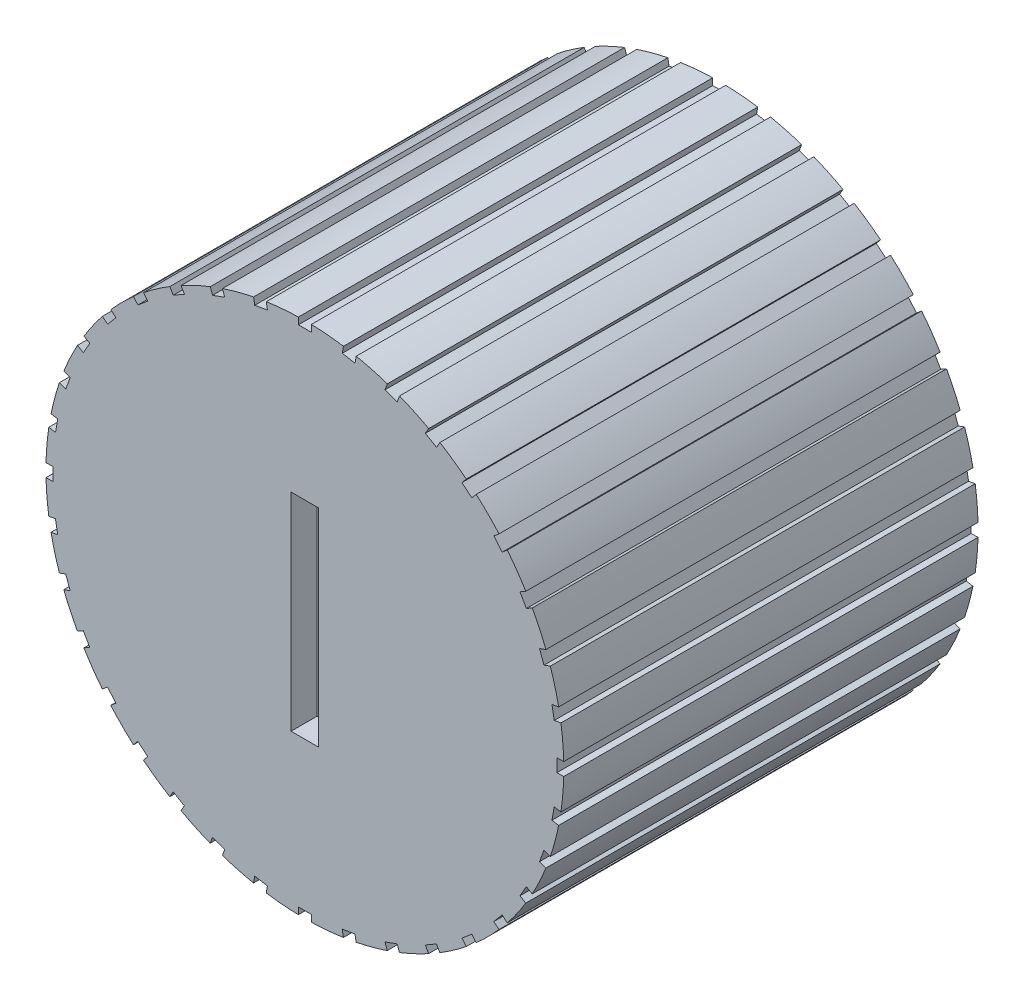
SolidWorks part; units mm, degrees
ref_plane "Front Plane" through (0, 0, 0) normal (0, 0, 1) x (1, 0, 0)
ref_plane "Top Plane" through (0, 0, 0) normal (0, 1, 0) x (1, 0, 0)
ref_plane "Right Plane" through (0, 0, 0) normal (1, 0, 0) x (0, 0, -1)
sketch "Sketch1" plane through (0, 0, 0) normal (0, 1, 0) x (1, 0, 0)
  line L0 (10, 0) -> (0, 0)
  line L1 (0, 0) -> (0, -16)
  line L2 (0, -16) -> (10, -16)
  line L3 (10, -16) -> (10, 0)
  line L4 (0, 0) -> (0, -16) construction
revolve "Revolve1" add sketch "Sketch1" angle 360 about L4
sketch "Sketch2" plane through (0, 0, 16) normal (0, 0, 1) x (1, 0, 0)
  line L0 (-0.2484, 9.9969) -> (-0.2484, 9.7356)
  line L1 (-0.2484, 9.7356) -> (0.2513, 9.7356)
  line L2 (0.2513, 9.7356) -> (0.2513, 9.9968)
  arc A0 (0.2513, 9.9968) -> (-0.2484, 9.9969) centre (0, 0) ccw
extrude "Cut-Extrude1" cut sketch "Sketch2" against normal blind 16
sketch "Sketch3" plane through (0, 0, 16) normal (0, 0, 1) x (1, 0, 0)
  line L0 (1.4913, 9.8882) -> (1.4459, 9.6308)
  line L1 (1.4459, 9.6308) -> (1.938, 9.544)
  line L2 (1.938, 9.544) -> (1.9834, 9.8013)
  arc A0 (1.9834, 9.8013) -> (1.4913, 9.8882) centre (0, 0) ccw
extrude "Cut-Extrude2" cut sketch "Sketch3" against normal blind 16
sketch "Sketch4" plane through (0, 0, 16) normal (0, 0, 1) x (1, 0, 0)
  line L0 (3.1857, 9.479) -> (3.0963, 9.2334)
  line L1 (3.0963, 9.2334) -> (3.5659, 9.0625)
  line L2 (3.5659, 9.0625) -> (3.6552, 9.308)
  arc A0 (3.6552, 9.308) -> (3.1857, 9.479) centre (0, 0) ccw
extrude "Cut-Extrude3" cut sketch "Sketch4" against normal blind 16
sketch "Sketch5" plane through (0, 0, 16) normal (0, 0, 1) x (1, 0, 0)
  line L0 (4.7833, 8.7818) -> (4.6526, 8.5554)
  line L1 (4.6526, 8.5554) -> (5.0854, 8.3056)
  line L2 (5.0854, 8.3056) -> (5.216, 8.5319)
  arc A0 (5.216, 8.5319) -> (4.7833, 8.7818) centre (0, 0) ccw
extrude "Cut-Extrude4" cut sketch "Sketch5" against normal blind 16
sketch "Sketch6" plane through (0, 0, 16) normal (0, 0, 1) x (1, 0, 0)
  line L0 (6.2356, 7.8178) -> (6.0676, 7.6176)
  line L1 (6.0676, 7.6176) -> (6.4504, 7.2963)
  line L2 (6.4504, 7.2963) -> (6.6183, 7.4965)
  arc A0 (6.6183, 7.4965) -> (6.2356, 7.8178) centre (0, 0) ccw
extrude "Cut-Extrude5" cut sketch "Sketch6" against normal blind 16
sketch "Sketch7" plane through (0, 0, 16) normal (0, 0, 1) x (1, 0, 0)
  line L0 (7.4984, 6.6162) -> (7.2982, 6.4482)
  line L1 (7.2982, 6.4482) -> (7.6194, 6.0654)
  line L2 (7.6194, 6.0654) -> (7.8195, 6.2334)
  arc A0 (7.8195, 6.2334) -> (7.4984, 6.6162) centre (0, 0) ccw
extrude "Cut-Extrude6" cut sketch "Sketch7" against normal blind 16
sketch "Sketch8" plane through (0, 0, 16) normal (0, 0, 1) x (1, 0, 0)
  line L0 (8.5334, 5.2136) -> (8.307, 5.0829)
  line L1 (8.307, 5.0829) -> (8.5569, 4.6502)
  line L2 (8.5569, 4.6502) -> (8.7832, 4.7808)
  arc A0 (8.7832, 4.7808) -> (8.5334, 5.2136) centre (0, 0) ccw
extrude "Cut-Extrude7" cut sketch "Sketch8" against normal blind 16
sketch "Sketch9" plane through (0, 0, 16) normal (0, 0, 1) x (1, 0, 0)
  line L0 (9.3091, 3.6526) -> (9.0635, 3.5632)
  line L1 (9.0635, 3.5632) -> (9.2344, 3.0936)
  line L2 (9.2344, 3.0936) -> (9.4799, 3.183)
  arc A0 (9.4799, 3.183) -> (9.3091, 3.6526) centre (0, 0) ccw
extrude "Cut-Extrude8" cut sketch "Sketch9" against normal blind 16
sketch "Sketch10" plane through (0, 0, 16) normal (0, 0, 1) x (1, 0, 0)
  line L0 (9.8019, 1.9806) -> (9.5445, 1.9352)
  line L1 (9.5445, 1.9352) -> (9.6313, 1.4431)
  line L2 (9.6313, 1.4431) -> (9.8886, 1.4885)
  arc A0 (9.8886, 1.4885) -> (9.8019, 1.9806) centre (0, 0) ccw
extrude "Cut-Extrude9" cut sketch "Sketch10" against normal blind 16
sketch "Sketch11" plane through (0, 0, 16) normal (0, 0, 1) x (1, 0, 0)
  line L0 (9.9969, 0.2484) -> (9.7356, 0.2484)
  line L1 (9.7356, 0.2484) -> (9.7356, -0.2513)
  line L2 (9.7356, -0.2513) -> (9.9968, -0.2513)
  arc A0 (9.9968, -0.2513) -> (9.9969, 0.2484) centre (0, 0) ccw
extrude "Cut-Extrude10" cut sketch "Sketch11" against normal blind 16
sketch "Sketch12" plane through (0, 0, 16) normal (0, 0, 1) x (1, 0, 0)
  line L0 (9.8882, -1.4913) -> (9.6308, -1.4459)
  line L1 (9.6308, -1.4459) -> (9.544, -1.938)
  line L2 (9.544, -1.938) -> (9.8013, -1.9834)
  arc A0 (9.8013, -1.9834) -> (9.8882, -1.4913) centre (0, 0) ccw
extrude "Cut-Extrude11" cut sketch "Sketch12" against normal blind 16
sketch "Sketch13" plane through (0, 0, 16) normal (0, 0, 1) x (1, 0, 0)
  line L0 (9.479, -3.1857) -> (9.2334, -3.0963)
  line L1 (9.2334, -3.0963) -> (9.0625, -3.5659)
  line L2 (9.0625, -3.5659) -> (9.308, -3.6552)
  arc A0 (9.308, -3.6552) -> (9.479, -3.1857) centre (0, 0) ccw
extrude "Cut-Extrude12" cut sketch "Sketch13" against normal blind 16
sketch "Sketch14" plane through (0, 0, 16) normal (0, 0, 1) x (1, 0, 0)
  line L0 (8.7818, -4.7833) -> (8.5554, -4.6526)
  line L1 (8.5554, -4.6526) -> (8.3056, -5.0854)
  line L2 (8.3056, -5.0854) -> (8.5319, -5.216)
  arc A0 (8.5319, -5.216) -> (8.7818, -4.7833) centre (0, 0) ccw
extrude "Cut-Extrude13" cut sketch "Sketch14" against normal blind 16
sketch "Sketch15" plane through (0, 0, 16) normal (0, 0, 1) x (1, 0, 0)
  line L0 (7.8178, -6.2356) -> (7.6176, -6.0676)
  line L1 (7.6176, -6.0676) -> (7.2963, -6.4504)
  line L2 (7.2963, -6.4504) -> (7.4965, -6.6183)
  arc A0 (7.4965, -6.6183) -> (7.8178, -6.2356) centre (0, 0) ccw
extrude "Cut-Extrude14" cut sketch "Sketch15" against normal blind 16
sketch "Sketch16" plane through (0, 0, 16) normal (0, 0, 1) x (1, 0, 0)
  line L0 (6.6162, -7.4984) -> (6.4482, -7.2982)
  line L1 (6.4482, -7.2982) -> (6.0654, -7.6194)
  line L2 (6.0654, -7.6194) -> (6.2334, -7.8195)
  arc A0 (6.2334, -7.8195) -> (6.6162, -7.4984) centre (0, 0) ccw
extrude "Cut-Extrude15" cut sketch "Sketch16" against normal blind 16
sketch "Sketch17" plane through (0, 0, 16) normal (0, 0, 1) x (1, 0, 0)
  line L0 (5.2136, -8.5334) -> (5.0829, -8.307)
  line L1 (5.0829, -8.307) -> (4.6502, -8.5569)
  line L2 (4.6502, -8.5569) -> (4.7808, -8.7832)
  arc A0 (4.7808, -8.7832) -> (5.2136, -8.5334) centre (0, 0) ccw
extrude "Cut-Extrude16" cut sketch "Sketch17" against normal blind 16
sketch "Sketch18" plane through (0, 0, 16) normal (0, 0, 1) x (1, 0, 0)
  line L0 (3.6526, -9.3091) -> (3.5632, -9.0635)
  line L1 (3.5632, -9.0635) -> (3.0936, -9.2344)
  line L2 (3.0936, -9.2344) -> (3.183, -9.4799)
  arc A0 (3.183, -9.4799) -> (3.6526, -9.3091) centre (0, 0) ccw
extrude "Cut-Extrude17" cut sketch "Sketch18" against normal blind 16
sketch "Sketch19" plane through (0, 0, 16) normal (0, 0, 1) x (1, 0, 0)
  line L0 (1.9806, -9.8019) -> (1.9352, -9.5445)
  line L1 (1.9352, -9.5445) -> (1.4431, -9.6313)
  line L2 (1.4431, -9.6313) -> (1.4885, -9.8886)
  arc A0 (1.4885, -9.8886) -> (1.9806, -9.8019) centre (0, 0) ccw
extrude "Cut-Extrude18" cut sketch "Sketch19" against normal blind 16
sketch "Sketch20" plane through (0, 0, 16) normal (0, 0, 1) x (1, 0, 0)
  line L0 (0.2484, -9.9969) -> (0.2484, -9.7356)
  line L1 (0.2484, -9.7356) -> (-0.2513, -9.7356)
  line L2 (-0.2513, -9.7356) -> (-0.2513, -9.9968)
  arc A0 (-0.2513, -9.9968) -> (0.2484, -9.9969) centre (0, 0) ccw
extrude "Cut-Extrude19" cut sketch "Sketch20" against normal blind 16
sketch "Sketch21" plane through (0, 0, 16) normal (0, 0, 1) x (1, 0, 0)
  line L0 (-1.4913, -9.8882) -> (-1.4459, -9.6308)
  line L1 (-1.4459, -9.6308) -> (-1.938, -9.544)
  line L2 (-1.938, -9.544) -> (-1.9834, -9.8013)
  arc A0 (-1.9834, -9.8013) -> (-1.4913, -9.8882) centre (0, 0) ccw
extrude "Cut-Extrude20" cut sketch "Sketch21" against normal blind 16
sketch "Sketch22" plane through (0, 0, 16) normal (0, 0, 1) x (1, 0, 0)
  line L0 (-3.1857, -9.479) -> (-3.0963, -9.2334)
  line L1 (-3.0963, -9.2334) -> (-3.5659, -9.0625)
  line L2 (-3.5659, -9.0625) -> (-3.6552, -9.308)
  arc A0 (-3.6552, -9.308) -> (-3.1857, -9.479) centre (0, 0) ccw
extrude "Cut-Extrude21" cut sketch "Sketch22" against normal blind 16
sketch "Sketch23" plane through (0, 0, 16) normal (0, 0, 1) x (1, 0, 0)
  line L0 (-4.7833, -8.7818) -> (-4.6526, -8.5554)
  line L1 (-4.6526, -8.5554) -> (-5.0854, -8.3056)
  line L2 (-5.0854, -8.3056) -> (-5.216, -8.5319)
  arc A0 (-5.216, -8.5319) -> (-4.7833, -8.7818) centre (0, 0) ccw
extrude "Cut-Extrude22" cut sketch "Sketch23" against normal blind 16
sketch "Sketch24" plane through (0, 0, 16) normal (0, 0, 1) x (1, 0, 0)
  line L0 (-6.2356, -7.8178) -> (-6.0676, -7.6176)
  line L1 (-6.0676, -7.6176) -> (-6.4504, -7.2963)
  line L2 (-6.4504, -7.2963) -> (-6.6183, -7.4965)
  arc A0 (-6.6183, -7.4965) -> (-6.2356, -7.8178) centre (0, 0) ccw
extrude "Cut-Extrude23" cut sketch "Sketch24" against normal blind 16
sketch "Sketch25" plane through (0, 0, 16) normal (0, 0, 1) x (1, 0, 0)
  line L0 (-7.4984, -6.6162) -> (-7.2982, -6.4482)
  line L1 (-7.2982, -6.4482) -> (-7.6194, -6.0654)
  line L2 (-7.6194, -6.0654) -> (-7.8195, -6.2334)
  arc A0 (-7.8195, -6.2334) -> (-7.4984, -6.6162) centre (0, 0) ccw
extrude "Cut-Extrude24" cut sketch "Sketch25" against normal blind 16
sketch "Sketch26" plane through (0, 0, 16) normal (0, 0, 1) x (1, 0, 0)
  line L0 (-8.5334, -5.2136) -> (-8.307, -5.0829)
  line L1 (-8.307, -5.0829) -> (-8.5569, -4.6502)
  line L2 (-8.5569, -4.6502) -> (-8.7832, -4.7808)
  arc A0 (-8.7832, -4.7808) -> (-8.5334, -5.2136) centre (0, 0) ccw
extrude "Cut-Extrude25" cut sketch "Sketch26" against normal blind 16
sketch "Sketch27" plane through (0, 0, 16) normal (0, 0, 1) x (1, 0, 0)
  line L0 (-9.3091, -3.6526) -> (-9.0635, -3.5632)
  line L1 (-9.0635, -3.5632) -> (-9.2344, -3.0936)
  line L2 (-9.2344, -3.0936) -> (-9.4799, -3.183)
  arc A0 (-9.4799, -3.183) -> (-9.3091, -3.6526) centre (0, 0) ccw
extrude "Cut-Extrude26" cut sketch "Sketch27" against normal blind 16
sketch "Sketch28" plane through (0, 0, 16) normal (0, 0, 1) x (1, 0, 0)
  line L0 (-9.8019, -1.9806) -> (-9.5445, -1.9352)
  line L1 (-9.5445, -1.9352) -> (-9.6313, -1.4431)
  line L2 (-9.6313, -1.4431) -> (-9.8886, -1.4885)
  arc A0 (-9.8886, -1.4885) -> (-9.8019, -1.9806) centre (0, 0) ccw
extrude "Cut-Extrude27" cut sketch "Sketch28" against normal blind 16
sketch "Sketch29" plane through (0, 0, 16) normal (0, 0, 1) x (1, 0, 0)
  line L0 (-9.9969, -0.2484) -> (-9.7356, -0.2484)
  line L1 (-9.7356, -0.2484) -> (-9.7356, 0.2513)
  line L2 (-9.7356, 0.2513) -> (-9.9968, 0.2513)
  arc A0 (-9.9968, 0.2513) -> (-9.9969, -0.2484) centre (0, 0) ccw
extrude "Cut-Extrude28" cut sketch "Sketch29" against normal blind 16
sketch "Sketch30" plane through (0, 0, 16) normal (0, 0, 1) x (1, 0, 0)
  line L0 (-9.8882, 1.4913) -> (-9.6308, 1.4459)
  line L1 (-9.6308, 1.4459) -> (-9.544, 1.938)
  line L2 (-9.544, 1.938) -> (-9.8013, 1.9834)
  arc A0 (-9.8013, 1.9834) -> (-9.8882, 1.4913) centre (0, 0) ccw
extrude "Cut-Extrude29" cut sketch "Sketch30" against normal blind 16
sketch "Sketch31" plane through (0, 0, 16) normal (0, 0, 1) x (1, 0, 0)
  line L0 (-9.479, 3.1857) -> (-9.2334, 3.0963)
  line L1 (-9.2334, 3.0963) -> (-9.0625, 3.5659)
  line L2 (-9.0625, 3.5659) -> (-9.308, 3.6552)
  arc A0 (-9.308, 3.6552) -> (-9.479, 3.1857) centre (0, 0) ccw
extrude "Cut-Extrude30" cut sketch "Sketch31" against normal blind 16
sketch "Sketch32" plane through (0, 0, 16) normal (0, 0, 1) x (1, 0, 0)
  line L0 (-8.7818, 4.7833) -> (-8.5554, 4.6526)
  line L1 (-8.5554, 4.6526) -> (-8.3056, 5.0854)
  line L2 (-8.3056, 5.0854) -> (-8.5319, 5.216)
  arc A0 (-8.5319, 5.216) -> (-8.7818, 4.7833) centre (0, 0) ccw
extrude "Cut-Extrude31" cut sketch "Sketch32" against normal blind 16
sketch "Sketch33" plane through (0, 0, 16) normal (0, 0, 1) x (1, 0, 0)
  line L0 (-7.8178, 6.2356) -> (-7.6176, 6.0676)
  line L1 (-7.6176, 6.0676) -> (-7.2963, 6.4504)
  line L2 (-7.2963, 6.4504) -> (-7.4965, 6.6183)
  arc A0 (-7.4965, 6.6183) -> (-7.8178, 6.2356) centre (0, 0) ccw
extrude "Cut-Extrude32" cut sketch "Sketch33" against normal blind 16
sketch "Sketch34" plane through (0, 0, 16) normal (0, 0, 1) x (1, 0, 0)
  line L0 (-6.6162, 7.4984) -> (-6.4482, 7.2982)
  line L1 (-6.4482, 7.2982) -> (-6.0654, 7.6194)
  line L2 (-6.0654, 7.6194) -> (-6.2334, 7.8195)
  arc A0 (-6.2334, 7.8195) -> (-6.6162, 7.4984) centre (0, 0) ccw
extrude "Cut-Extrude33" cut sketch "Sketch34" against normal blind 16
sketch "Sketch35" plane through (0, 0, 16) normal (0, 0, 1) x (1, 0, 0)
  line L0 (-5.2136, 8.5334) -> (-5.0829, 8.307)
  line L1 (-5.0829, 8.307) -> (-4.6502, 8.5569)
  line L2 (-4.6502, 8.5569) -> (-4.7808, 8.7832)
  arc A0 (-4.7808, 8.7832) -> (-5.2136, 8.5334) centre (0, 0) ccw
extrude "Cut-Extrude34" cut sketch "Sketch35" against normal blind 16
sketch "Sketch36" plane through (0, 0, 16) normal (0, 0, 1) x (1, 0, 0)
  line L0 (-3.6526, 9.3091) -> (-3.5632, 9.0635)
  line L1 (-3.5632, 9.0635) -> (-3.0936, 9.2344)
  line L2 (-3.0936, 9.2344) -> (-3.183, 9.4799)
  arc A0 (-3.183, 9.4799) -> (-3.6526, 9.3091) centre (0, 0) ccw
extrude "Cut-Extrude35" cut sketch "Sketch36" against normal blind 16
sketch "Sketch37" plane through (0, 0, 16) normal (0, 0, 1) x (1, 0, 0)
  line L0 (-1.9806, 9.8019) -> (-1.9352, 9.5445)
  line L1 (-1.9352, 9.5445) -> (-1.4431, 9.6313)
  line L2 (-1.4431, 9.6313) -> (-1.4885, 9.8886)
  arc A0 (-1.4885, 9.8886) -> (-1.9806, 9.8019) centre (0, 0) ccw
extrude "Cut-Extrude36" cut sketch "Sketch37" against normal blind 16
sketch "Sketch38" plane through (0, 0, 16) normal (0, 0, 1) x (1, 0, 0)
  line L0 (-0.5329, -3.9995) -> (0.5257, -4.0005)
  line L1 (0.5257, -4.0005) -> (0.5329, 3.9995)
  line L2 (0.5329, 3.9995) -> (-0.5257, 4.0005)
  line L3 (-0.5257, 4.0005) -> (-0.5329, -3.9995)
extrude "Cut-Extrude37" cut sketch "Sketch38" against normal blind 1
hole_wizard "Ø6.0 (6) Diameter Hole1" positions "Sketch40" profile "Sketch39" hole size "Ø6.0" standard "ANSI Metric"
sketch "Sketch40" plane through (0, 0, 0) normal (0, 0, -1) x (-1, 0, 0)
  point P0 (0, 0)
sketch "Sketch39" plane through (0, 0, 0) normal (1, 0, 0) x (0, 1, 0)
  line L0 (0, 0) -> (0, 14)
  line L1 (0, 14) -> (3, 14)
  line L2 (3, 14) -> (3, 0)
  line L5 (3, 0) -> (0, 0)
  line L10 (0, 14) -> (-3, 14) construction
  line L11 (0, -6.35) -> (0, 107.95) construction
  dimension "Hole Dia." = 6
  dimension "Hole Depth" = 14
  dimension "Drill Angle" = 180
